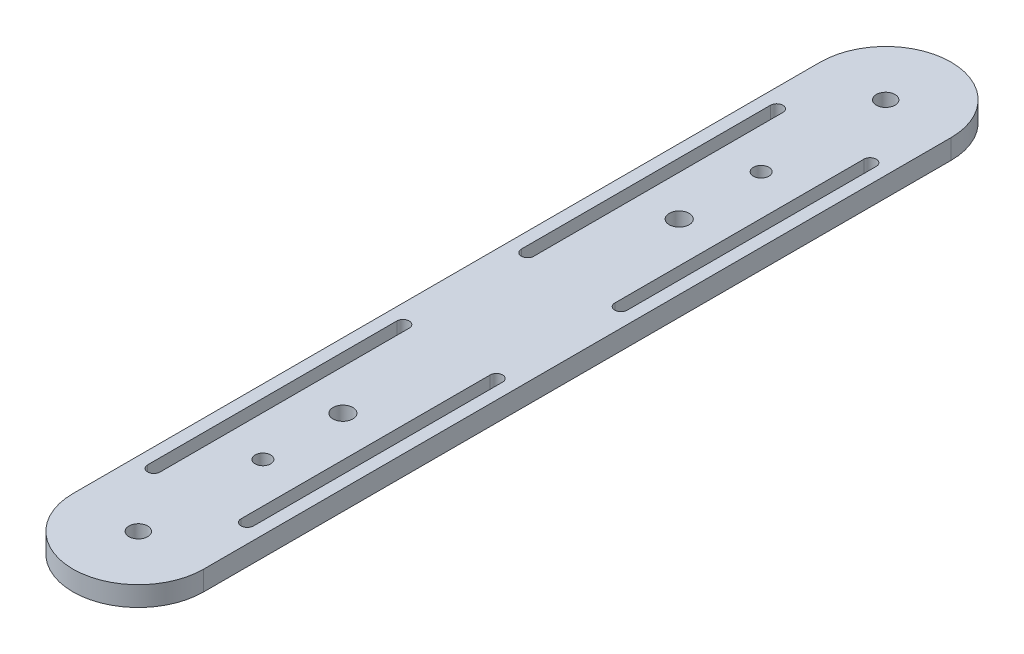
SolidWorks part; units mm, degrees
ref_plane "Front Plane" through (0, 0, 0) normal (0, 0, 1) x (1, 0, 0)
ref_plane "Top Plane" through (0, 0, 0) normal (0, 1, 0) x (1, 0, 0)
ref_plane "Right Plane" through (0, 0, 0) normal (1, 0, 0) x (0, 0, -1)
sketch "Sketch1" plane through (0, 0, 0) normal (0, 1, 0) x (1, 0, 0)
  line L0 (-10.5, 0) -> (-10.5, -120)
  line L1 (10.5, 0) -> (10.5, -120)
  arc A0 (10.5, 0) -> (-10.5, 0) centre (0, 0) ccw
  arc A1 (-10.5, -120) -> (10.5, -120) centre (0, -120) ccw
  circle A2 centre (0, 0) radius 1.5
  circle A5 centre (0, -120) radius 1.5
  dimension "D1" = 10.5
  dimension "D3" = 3
  dimension "D2" = 120
extrude "Boss-Extrude1" add sketch "Sketch1" along normal blind 3.175
sketch "Sketch2" plane through (0, 0, 0) normal (0, -1, 0) x (1, 0, 0)
  arc A0 (0, 18.75) -> (0, 21.25) centre (0, 20) ccw construction
  arc A1 (0, 21.25) -> (0, 18.75) centre (0, 20) ccw construction
  arc A4 (0, 18.75) -> (0, 21.25) centre (0, 20) ccw
  arc A5 (0, 21.25) -> (0, 18.75) centre (0, 20) ccw
extrude "Cut-Extrude1" cut sketch "Sketch2" against normal through all both and the other way through all
sketch "Sketch3" plane through (0, 3.175, 0) normal (0, 1, 0) x (1, 0, 0)
  arc A2 (0, -98.75) -> (0, -101.25) centre (0, -100) ccw construction
  arc A3 (0, -101.25) -> (0, -98.75) centre (0, -100) ccw construction
  arc A6 (0, -98.75) -> (0, -101.25) centre (0, -100) ccw
  arc A7 (0, -101.25) -> (0, -98.75) centre (0, -100) ccw
extrude "Cut-Extrude2" cut sketch "Sketch3" against normal through all both and the other way through all
sketch "Sketch4" plane through (0, 3.175, 0) normal (0, 1, 0) x (1, 0, 0)
  circle A0 centre (0, -33.15) radius 1.6 construction
  circle A1 centre (0, -87.15) radius 1.6 construction
  circle A2 centre (0, -33.15) radius 1.6
  circle A3 centre (0, -87.15) radius 1.6
extrude "Cut-Extrude3" cut sketch "Sketch4" against normal through all both and the other way through all
sketch "Sketch5" plane through (0, 0, 0) normal (0, -1, 0) x (1, 0, 0)
  line L0 (0, -10.5) -> (0, 130.5) construction
  line L1 (-10.5, 60) -> (10.5, 60) construction
  line L2 (-10.5, 0) -> (-10.5, 120) construction
  line L3 (10.5, 120) -> (10.5, 0) construction
  line L6 (-8.5, 10) -> (-8.5, 50)
  line L7 (-6.5, 50) -> (-6.5, 10)
  line L8 (6.5, 50) -> (6.5, 10)
  line L9 (8.5, 10) -> (8.5, 50)
  line L22 (8.5, 110) -> (8.5, 70)
  line L23 (6.5, 70) -> (6.5, 110)
  line L24 (-6.5, 70) -> (-6.5, 110)
  line L25 (-8.5, 110) -> (-8.5, 70)
  arc A0 (-10.5, 0) -> (10.5, 0) centre (0, 0) ccw construction
  arc A1 (10.5, 120) -> (-10.5, 120) centre (0, 120) ccw construction
  arc A4 (-8.5, 10) -> (-6.5, 10) centre (-7.5, 10) ccw
  arc A5 (-6.5, 50) -> (-8.5, 50) centre (-7.5, 50) ccw
  arc A6 (6.5, 50) -> (8.5, 50) centre (7.5, 50) cw
  arc A7 (8.5, 10) -> (6.5, 10) centre (7.5, 10) cw
  arc A20 (8.5, 110) -> (6.5, 110) centre (7.5, 110) ccw
  arc A21 (6.5, 70) -> (8.5, 70) centre (7.5, 70) ccw
  arc A22 (-6.5, 70) -> (-8.5, 70) centre (-7.5, 70) cw
  arc A23 (-8.5, 110) -> (-6.5, 110) centre (-7.5, 110) cw
  dimension "D1" = 40
  dimension "D3" = 10
  dimension "D2" = 2
  dimension "D4" = 3
extrude "Cut-Extrude4" cut sketch "Sketch5" against normal blind 40
